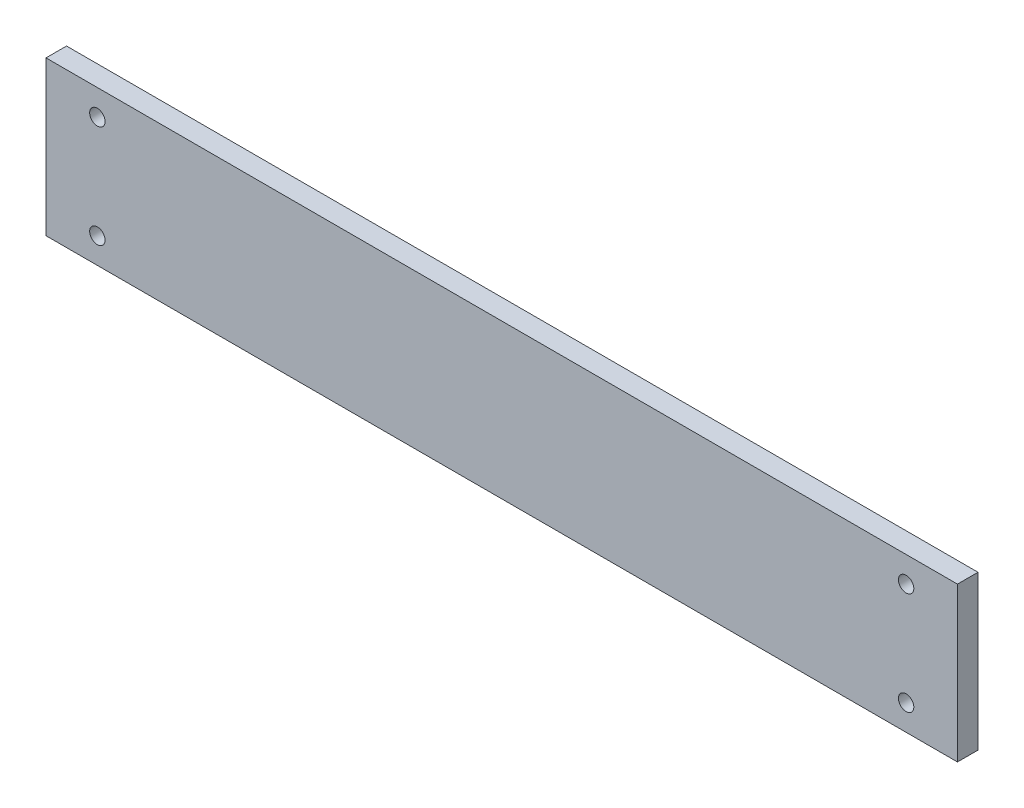
SolidWorks part; units mm, degrees
ref_plane "前视基准面" through (0, 0, 0) normal (0, 0, 1) x (1, 0, 0)
ref_plane "上视基准面" through (0, 0, 0) normal (0, 1, 0) x (1, 0, 0)
ref_plane "右视基准面" through (0, 0, 0) normal (1, 0, 0) x (0, 0, -1)
sketch "草图1" plane through (0, 0, 0) normal (0, 0, 1) x (1, 0, 0)
  line L0 (-106.324, 42.1977) -> (71.176, 42.1977)
  line L1 (71.176, 42.1977) -> (71.176, 12.1977)
  line L2 (71.176, 12.1977) -> (-106.324, 12.1977)
  line L3 (-106.324, 12.1977) -> (-106.324, 42.1977)
  line L4 (-96.324, 37.1977) -> (-96.324, 17.1977) construction
  line L5 (-96.324, 27.1977) -> (-28.5252, 27.1977) construction
  circle A0 centre (-96.324, 37.1977) radius 1.5
  circle A1 centre (-96.324, 17.1977) radius 1.5
  circle A2 centre (61.176, 37.1977) radius 1.5
  circle A3 centre (61.176, 17.1977) radius 1.5
  dimension "D1" = 15
  dimension "D2" = 15
  dimension "D3" = 177.5
  dimension "D4" = 10
  dimension "D5" = 10
extrude "凸台-拉伸1" add sketch "草图1" along normal blind 4
